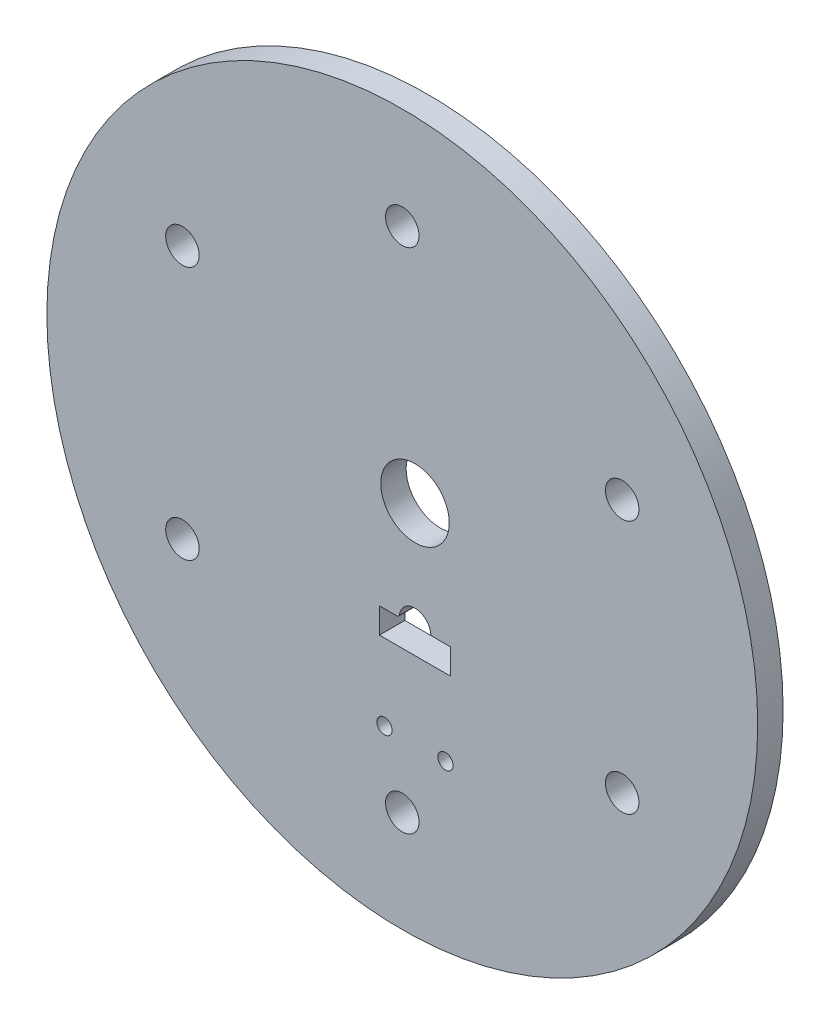
SolidWorks part; units mm, degrees
ref_plane "Front Plane" through (0, 0, 0) normal (0, 0, 1) x (1, 0, 0)
ref_plane "Top Plane" through (0, 0, 0) normal (0, 1, 0) x (1, 0, 0)
ref_plane "Right Plane" through (0, 0, 0) normal (1, 0, 0) x (0, 0, -1)
sketch "Sketch1" plane through (0, 0, 0) normal (0, 0, 1) x (1, 0, 0)
  circle A0 centre (0, 0) radius 70
  dimension "D1" = 140
extrude "Boss-Extrude1" add sketch "Sketch1" along normal blind 5
sketch "Sketch2" plane through (0, 0, 0) normal (0, 0, 1) x (1, 0, 0)
  line L0 (0, -2.75) -> (0, 2.75) construction
  line L1 (2.75, 0) -> (-2.75, 0) construction
  line L2 (-25, 30) -> (25, 30) construction
  line L3 (-25, 30) -> (-25, -30) construction
  line L4 (-25, -30) -> (25, -30) construction
  line L5 (25, 30) -> (25, -30) construction
  line L6 (-25, 30) -> (25, -30) construction
  line L7 (-25, -30) -> (25, 30) construction
  line L9 (-28.5, 30) -> (21.5, 30) construction
  line L10 (-28.5, 30) -> (-28.5, -30) construction
  line L11 (-28.5, -30) -> (21.5, -30) construction
  line L12 (21.5, 30) -> (21.5, -30) construction
  line L13 (-28.5, 30) -> (21.5, -30) construction
  line L14 (-28.5, -30) -> (21.5, 30) construction
  circle A0 centre (-3.5, 0) radius 3.175
  circle A1 centre (-3.5, -15) radius 2.5
  point P7 (0, 0)
  point P19 (-3.5, 0)
  dimension "D1" = 6.35
  dimension "D2" = 5
  dimension "D3" = 15
  dimension "D4" = 50
  dimension "D5" = 60
  dimension "D6" = 3.5
  dimension "D7" = 50
  dimension "D8" = 60
extrude "Cut-Extrude1" [suppressed] cut sketch "Sketch2" along normal through all
sketch "Sketch3" plane through (0, 0, 0) normal (1, 0, 0) x (0, 0, -1)
  line L0 (-46.5057, 0) -> (36.7778, 0) construction
sketch "Sketch4" plane through (0, 0, 0) normal (0, 0, 1) x (1, 0, 0)
  line L0 (0, -2.75) -> (0, 2.75) construction
  circle A0 centre (0, 50) radius 3
  dimension "D1" = 6
  dimension "D2" = 50
extrude "Cut-Extrude2" cut sketch "Sketch4" along normal through all
pattern_circular "CirPattern1" count 6 over 360 about axis through (0, 0, 0) along (0, 0, 1) of "Cut-Extrude2"
hole_wizard "M6 Clearance Hole1" positions "Sketch5" profile "Sketch6" hole size "M6" standard "ANSI Metric" end condition through all
sketch "Sketch5" plane through (0, 0, 5) normal (0, 0, 1) x (1, 0, 0)
  point P0 (0, 50)
  point P3 (43.3013, 25)
  point P6 (43.3013, -25)
  point P9 (0, -50)
  point P12 (-43.3013, -25)
  point P15 (-43.3013, 25)
sketch "Sketch6" plane through (0, 50, 5) normal (1, 0, 0) x (0, -1, 0)
  line L0 (0, 0) -> (0, 5)
  line L1 (0, 5) -> (3.3, 5)
  line L2 (3.3, 5) -> (3.3, 0)
  line L5 (3.3, 0) -> (0, 0)
  line L11 (0, -6.35) -> (0, 107.95) construction
  dimension "Thru Hole Dia." = 6.6
  dimension "Thru Hole Depth" = 5
sketch "Sketch7" plane through (0, 0, 0) normal (0, 0, 1) x (1, 0, 0)
  line L1 (9.5, -17) -> (-4.5, -17)
  line L2 (9.5, -17) -> (9.5, -22)
  line L3 (9.5, -22) -> (-4.5, -22)
  line L4 (-4.5, -17) -> (-4.5, -22)
  line L5 (9.5, -17) -> (-4.5, -22) construction
  line L6 (9.5, -22) -> (-4.5, -17) construction
  line L7 (9.5, 22) -> (-9.5, 22) construction
  line L8 (9.5, 22) -> (9.5, -22) construction
  line L9 (9.5, -22) -> (-9.5, -22) construction
  line L10 (-9.5, 22) -> (-9.5, -22) construction
  line L11 (9.5, 22) -> (-9.5, -22) construction
  line L12 (9.5, -22) -> (-9.5, 22) construction
  point P0 (2.5, -19.5)
  point P5 (0, 0)
  dimension "D2" = 14
  dimension "D3" = 5
  dimension "D4" = 19
  dimension "D5" = 44
extrude "Cut-Extrude3" cut sketch "Sketch7" along normal through all
sketch "Sketch8" plane through (0, 0, 0) normal (0, 0, -1) x (-1, 0, 0)
  line L0 (-2.5, -17) -> (-2.5, 46.2304) construction
  line L1 (-9.5, -17) -> (4.5, -17) construction
  line L3 (-9.5, -22) -> (9.5, -22) construction
  line L4 (-9.5, -22) -> (-9.5, 22) construction
  line L5 (-9.5, 22) -> (9.5, 22) construction
  line L6 (9.5, -22) -> (9.5, 22) construction
  circle A0 centre (-2.5, -10) radius 2.5 construction
  circle A1 centre (-2.5, 4) radius 1
  circle A2 centre (-2.5, 18) radius 0.5 construction
  circle A3 centre (-2.5, -10) radius 6 construction
  circle A4 centre (-2.5, 4) radius 6.35 construction
  circle A5 centre (-2.5, 18) radius 6 construction
  circle A6 centre (-2.5, -17) radius 3.1
  dimension "D5" = 12
  dimension "2" = 2
  dimension "D6" = 1
  dimension "D7" = 6.2
  dimension "6" = 5
  dimension "D4" = 12
  dimension "D1" = 19
  dimension "D2" = 44
  dimension "D3" = 14
  dimension "7" = 7
  dimension "D8" = 4
extrude "Cut-Extrude4" cut sketch "Sketch8" against normal through all
hole_wizard "1/2 Clearance Hole1" positions "Sketch9" profile "Sketch10" hole size "1/2" standard "ANSI Inch" end condition through all
sketch "Sketch9" plane through (0, 0, 0) normal (0, 0, -1) x (-1, 0, 0)
  point P4 (-2.5, 4)
sketch "Sketch10" plane through (2.5, 4, 0) normal (1, 0, 0) x (0, 1, 0)
  line L0 (0, 0) -> (0, 5)
  line L1 (0, 5) -> (6.7462, 5)
  line L2 (6.7462, 5) -> (6.7462, 0)
  line L5 (6.7462, 0) -> (0, 0)
  line L11 (0, -6.35) -> (0, 107.95) construction
  dimension "Thru Hole Dia." = 13.4925
  dimension "Thru Hole Depth" = 5
hole_wizard "#39 (0.0995) Diameter Hole1" [suppressed] positions "Sketch16" profile "Sketch15" hole size "#39" standard "ANSI Inch"
sketch "Sketch16" plane through (0, 0, 0) normal (0, 0, -1) x (-1, 0, 0)
  point P0 (-2.5, 18)
sketch "Sketch15" plane through (2.5, 18, 0) normal (1, 0, 0) x (0, 1, 0)
  line L0 (0, 0) -> (0, 10)
  line L1 (0, 10) -> (1.2636, 10)
  line L2 (1.2636, 10) -> (1.2636, 0)
  line L5 (1.2636, 0) -> (0, 0)
  line L11 (0, -6.35) -> (0, 107.95) construction
  dimension "Thru Hole Dia." = 2.5273
  dimension "Thru Hole Depth" = 10
hole_wizard "M8x1.0 Tapped Hole1" [suppressed] positions "Sketch17" profile "Sketch18" tap size "M8x1.0" standard "ANSI Metric"
sketch "Sketch17" plane through (0, 0, 0) normal (0, 0, -1) x (-1, 0, 0)
  point P0 (-2.5, -10)
sketch "Sketch18" plane through (2.5, -10, 0) normal (1, 0, 0) x (0, 1, 0)
  line L0 (0, 0) -> (0, 21.103)
  line L1 (0, 21.103) -> (3.5, 19)
  line L2 (3.5, 19) -> (3.5, 0)
  line L5 (3.5, 0) -> (0, 0)
  line L10 (0, 21.103) -> (-3.5, 19) construction
  line L11 (0, -6.35) -> (0, 107.95) construction
  dimension "Tap Drill Dia." = 7
  dimension "Tap Drill Depth" = 19
  dimension "Drill Angle" = 118
cosmetic thread "Hole Thread1" [suppressed] parameters "D1"=16, "D2"=8
sketch "Sketch19" [suppressed] plane through (0, 0, 0) normal (0, 0, -1) x (-1, 0, 0)
  circle A0 centre (-2.5, -10) radius 5
  dimension "D1" = 10
extrude "Cut-Extrude5" [suppressed] cut sketch "Sketch19" against normal blind 3
fillet "Fillet1" radius 0.5 2 edges at (-0.6, -17, 2.5) (5.6, -17, 2.5)
sketch "Sketch20" plane through (0, 0, 0) normal (0, 0, -1) x (-1, 0, 0)
  line L0 (-2.5, -22) -> (-2.5, -42.4383) construction
  line L1 (4.5, -22) -> (-9.5, -22) construction
  circle A0 centre (-8.5, -37) radius 1.5
  circle A1 centre (3.5, -37) radius 1.5
  dimension "D1" = 3
  dimension "D2" = 6
  dimension "D3" = 15
extrude "Cut-Extrude6" cut sketch "Sketch20" against normal through all
